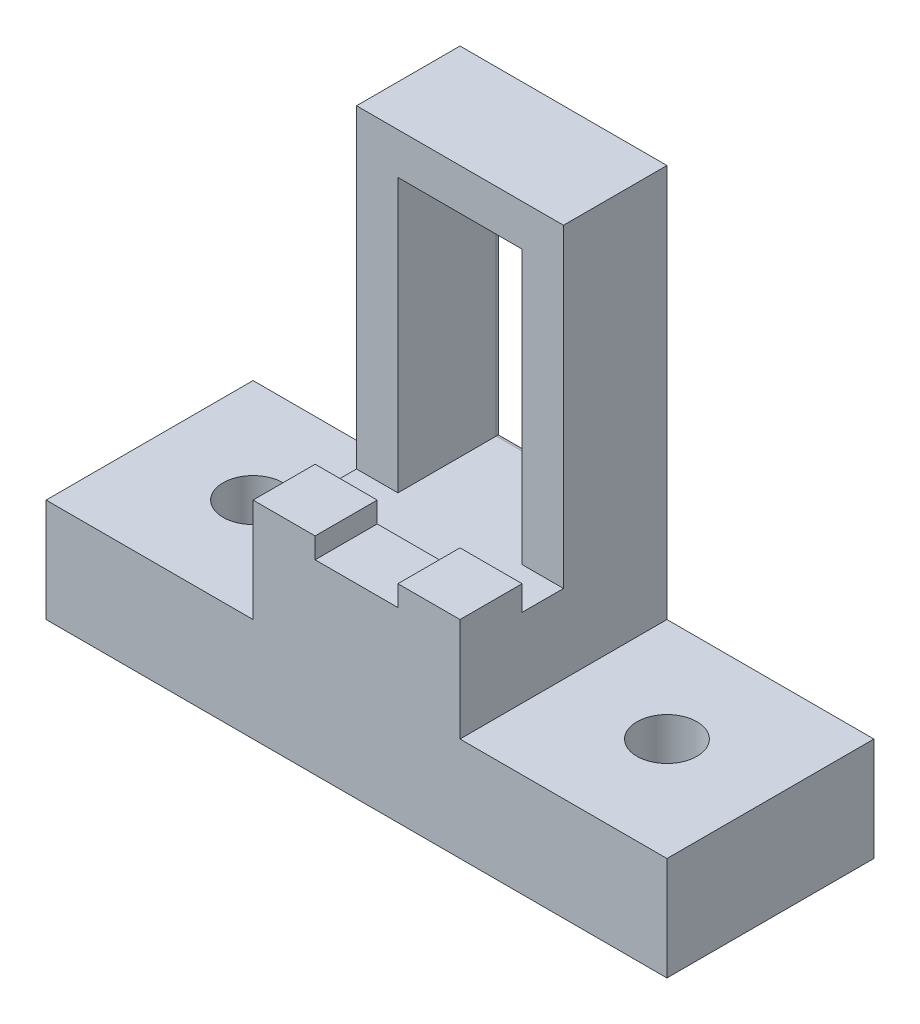
SolidWorks part; units mm, degrees
other "标注1"
sketch "草图8" plane through (-30, 24, -10.05) normal (-0.0333, 0.0376, -0.9987) x (-0.9561, 0.2897, 0.0428)
sketch "草图10" plane through (-30, 24, -10.05) normal (-0.0333, 0.0376, -0.9987) x (-0.9561, 0.2897, 0.0428)
sketch "草图23" plane through (-30, 24, -10) normal (-0.0333, 0.0376, -0.9987) x (-0.9561, 0.2897, 0.0428)
sketch "草图26" plane through (-30, 24, -10) normal (-0.0333, 0.0376, -0.9987) x (-0.9561, 0.2897, 0.0428)
sketch "草图30" plane through (-30, 24, -10) normal (-0.0333, 0.0376, -0.9987) x (-0.9561, 0.2897, 0.0428)
sketch "草图33" plane through (-30, 24, -10) normal (-0.0333, 0.0376, -0.9987) x (-0.9561, 0.2897, 0.0428)
other "标注2"
sketch "草图16" plane through (0, 24, 0) normal (0.8795, 0.3038, 0.3663) x (0.4513, -0.2881, -0.8446)
sketch "草图24" plane through (0, 24, 0) normal (0.8795, 0.3038, 0.3663) x (0.4513, -0.2881, -0.8446)
sketch "草图27" plane through (0, 24, 0) normal (0.8795, 0.3038, 0.3663) x (0.4513, -0.2881, -0.8446)
sketch "草图31" plane through (0, 24, 0) normal (0.8795, 0.3038, 0.3663) x (0.4513, -0.2881, -0.8446)
sketch "草图34" plane through (0, 24, 0) normal (0.8795, 0.3038, 0.3663) x (0.4513, -0.2881, -0.8446)
other "标注3"
sketch "草图17" plane through (0, 24, 0) normal (0.8795, 0.3038, 0.3663) x (0.4513, -0.2881, -0.8446)
sketch "草图25" plane through (0, 24, 0) normal (0.8795, 0.3038, 0.3663) x (0.4513, -0.2881, -0.8446)
sketch "草图28" plane through (0, 24, 0) normal (0.8795, 0.3038, 0.3663) x (0.4513, -0.2881, -0.8446)
sketch "草图32" plane through (0, 24, 0) normal (0.8795, 0.3038, 0.3663) x (0.4513, -0.2881, -0.8446)
sketch "草图35" plane through (0, 24, 0) normal (0.8795, 0.3038, 0.3663) x (0.4513, -0.2881, -0.8446)
ref_plane "前视基准面" through (0, 0, 0) normal (0, 0, 1) x (1, 0, 0)
ref_plane "上视基准面" through (0, 0, 0) normal (0, 1, 0) x (1, 0, 0)
ref_plane "右视基准面" through (0, 0, 0) normal (1, 0, 0) x (0, 0, -1)
other "Configuration Table"
sketch "草图1" plane through (0, 0, 0) normal (0, 1, 0) x (1, 0, 0)
  line L0 (-20, 0) -> (-20, -5)
  line L2 (0, 0) -> (0, 10)
  line L3 (0, 10) -> (-30, 10)
  line L4 (-30, 0) -> (-30, 10)
  line L5 (-20, -5) -> (-10, -5)
  line L6 (-10, -5) -> (-10, 0)
  line L7 (-30, 0) -> (-20, 0)
  line L8 (-10, 0) -> (0, 0)
  dimension "D1" = 10
  dimension "D2" = 30
  dimension "D3" = 10
  dimension "D4" = 10
  dimension "D5" = 5
  dimension "D6" = 5
extrude "凸台-拉伸1" add sketch "草图1" along normal blind 4
sketch "草图2" plane through (0, 4, 0) normal (0, 1, 0) x (1, 0, 0)
  line L7 (0, 10) -> (-30, 10) construction
  line L8 (-20, -5) -> (-10, -5)
  line L9 (-20, -5) -> (-20, 10)
  line L10 (-20, 10) -> (-10, 10)
  line L11 (-10, -5) -> (-10, 10)
extrude "凸台-拉伸2" add sketch "草图2" along normal blind 20
sketch "草图3" plane through (0, 4, 0) normal (0, 1, 0) x (1, 0, 0)
  line L0 (-20, 10) -> (-30, 10) construction
  line L1 (-30, 10) -> (-30, 0) construction
  line L2 (0, 10) -> (-10, 10) construction
  line L3 (0, 0) -> (0, 10) construction
  circle A0 centre (-25, 5) radius 1.45
  circle A1 centre (-5, 5) radius 1.45
  dimension "D1" = 5
  dimension "D2" = 5
  dimension "D3" = 5
  dimension "D4" = 5
  dimension "D5" = 2.9
  dimension "D6" = 2.9
extrude "切除-拉伸1" cut sketch "草图3" against normal blind 20
sketch "草图4" plane through (0, 0, -10) normal (0, 0, -1) x (-1, 0, 0)
  line L6 (10, 24) -> (10, 4) construction
  line L7 (12, 22) -> (18, 22)
  line L8 (12, 22) -> (12, 8.8)
  line L9 (12, 8.8) -> (18, 8.8)
  line L10 (18, 22) -> (18, 8.8)
  line L11 (10, 24) -> (20, 24) construction
  dimension "D1" = 6
  dimension "D2" = 13.2
  dimension "D3" = 2
  dimension "D4" = 2
extrude "切除-拉伸2" cut sketch "草图4" against normal blind 9.5
sketch "草图6" plane through (0, 0, -0.5) normal (0, 0, -1) x (-1, 0, 0)
  line L0 (15, 22) -> (15, 20.68) construction
  line L1 (18, 22) -> (12, 22) construction
  line L2 (15, 20.68) -> (15, 15.6) construction
  line L3 (15, 15.6) -> (15, 10.52) construction
  circle A0 centre (15, 20.68) radius 0.75
  circle A2 centre (15, 10.52) radius 0.75
  circle A3 centre (15, 15.6) radius 0.75
  dimension "D4" = 1.5
  dimension "D5" = 1.5
  dimension "D6" = 1.5
  dimension "D1" = 1.32
  dimension "D2" = 5.08
  dimension "D3" = 5.08
extrude "切除-拉伸4" cut sketch "草图6" against normal blind 3.5
sketch "草图7" plane through (0, 0, 5) normal (0, 0, 1) x (1, 0, 0)
  line L4 (-10, 24) -> (-20, 24)
  line L5 (-20, 24) -> (-20, 0)
  line L6 (-20, 0) -> (-10, 0)
  line L7 (-10, 0) -> (-10, 24)
  line L8 (-10, 24) -> (-20, 24)
  line L9 (-20, 24) -> (-20, 0)
  line L10 (-20, 0) -> (-10, 0)
  line L11 (-10, 0) -> (-10, 24)
  dimension "D1" = 0
extrude "切除-拉伸5" cut sketch "草图7" against normal blind 5
sketch "草图9" plane through (0, 0, -0.5) normal (0, 0, -1) x (-1, 0, 0)
  line L1 (13.5, 21.6) -> (16.5, 21.6)
  line L2 (13.5, 21.6) -> (13.5, 9.6)
  line L3 (13.5, 9.6) -> (16.5, 9.6)
  line L4 (16.5, 21.6) -> (16.5, 9.6)
  line L5 (13.5, 21.6) -> (16.5, 9.6) construction
  line L6 (13.5, 9.6) -> (16.5, 21.6) construction
  point P0 (15, 15.6)
  dimension "D1" = 3
  dimension "D2" = 12
extrude "切除-拉伸6" cut sketch "草图9" against normal blind 10
sketch "草图11" plane through (0, 0, -0.5) normal (0, 0, -1) x (-1, 0, 0)
  line L0 (18, 8.8) -> (18, 22) construction
  line L1 (16.5, 21.6) -> (18, 21.6)
  line L2 (16.5, 21.6) -> (16.5, 9.6)
  line L3 (16.5, 9.6) -> (18, 9.6)
  line L4 (18, 21.6) -> (18, 9.6)
  line L5 (12, 22) -> (12, 8.8) construction
  line L6 (13.5, 21.6) -> (12, 21.6)
  line L7 (13.5, 21.6) -> (13.5, 9.6)
  line L8 (13.5, 9.6) -> (12, 9.6)
  line L9 (12, 21.6) -> (12, 9.6)
extrude "切除-拉伸7" cut sketch "草图11" against normal blind 10
sketch "草图13" plane through (0, 24, 0) normal (0, 1, 0) x (1, 0, 0)
  line L0 (-10, 0) -> (-10, 10) construction
  line L1 (-20, 0) -> (-10, 0)
  line L2 (-20, 0) -> (-20, 5)
  line L3 (-20, 5) -> (-10, 5)
  line L4 (-10, 0) -> (-10, 5)
extrude "切除-拉伸8" cut sketch "草图13" against normal up to surface (20 mm away) up to face at (-5, 4, -3.55)
sketch "草图19" plane through (0, 4, 0) normal (0, 1, 0) x (1, 0, 0)
  line L1 (-20, 5) -> (-10, 5)
  line L2 (-20, 5) -> (-20, 2.6)
  line L3 (-20, 2.6) -> (-10, 2.6)
  line L4 (-10, 5) -> (-10, 2.6)
  dimension "D1" = 2.4
extrude "凸台-拉伸6" add sketch "草图19" along normal blind 4.8
sketch "草图20" plane through (0, 4, 0) normal (0, 1, 0) x (1, 0, 0)
  line L0 (-30, 0) -> (0, 0) construction
  line L1 (-20, 2.6) -> (-10, 2.6)
  line L2 (-20, 2.6) -> (-20, 0)
  line L3 (-20, 0) -> (-10, 0)
  line L4 (-10, 2.6) -> (-10, 0)
extrude "凸台-拉伸7" add sketch "草图20" along normal blind 6
fillet "圆角17" radius 0.25 4 edges at (-15, 8.8, -10) (-15, 22, -10) (-18, 15.4, -10) (-12, 15.4, -10)
sketch "草图21" plane through (0, 0, 0) normal (0, 0, 1) x (1, 0, 0)
  line L0 (-15, 10) -> (-15, 7.5151) construction
  line L1 (-20, 10) -> (-10, 10) construction
  line L2 (-13, 10) -> (-17, 10)
  line L3 (-17, 10) -> (-17, 9)
  line L4 (-17, 9) -> (-13, 9)
  line L5 (-13, 10) -> (-13, 9)
  point P9 (-15, 9)
  dimension "D1" = 2
  dimension "D2" = 1
extrude "切除-拉伸9" cut sketch "草图21" against normal blind 5.2
sketch "草图22" plane through (0, 0, -2.6) normal (0, 0, -1) x (-1, 0, 0)
  line L8 (17, 9) -> (13, 9)
  line L9 (13, 9) -> (13, 10)
  line L10 (13, 10) -> (10, 10)
  line L11 (10, 10) -> (10, 8.8)
  line L12 (10, 8.8) -> (20, 8.8)
  line L13 (20, 8.8) -> (20, 10)
  line L14 (20, 10) -> (17, 10)
  line L15 (17, 10) -> (17, 9)
  line L16 (17, 9) -> (13, 9)
  line L17 (13, 9) -> (13, 10)
  line L18 (13, 10) -> (10, 10)
  line L19 (10, 10) -> (10, 8.8)
  line L20 (10, 8.8) -> (20, 8.8)
  line L21 (20, 8.8) -> (20, 10)
  line L22 (20, 10) -> (17, 10)
  line L23 (17, 10) -> (17, 9)
  dimension "D1" = 0
extrude "凸台-拉伸8" add sketch "草图22" along normal blind 0.4
sketch "草图29" plane through (0, 4, 0) normal (0, 1, 0) x (1, 0, 0)
  line L0 (-30, 0) -> (-20, 0) construction
  line L1 (-20, 0) -> (-20, 10) construction
  line L2 (-20, 10) -> (-30, 10) construction
  line L3 (-30, 10) -> (-30, 0) construction
  line L4 (-10, 10) -> (-10, 0) construction
  line L5 (-10, 0) -> (0, 0) construction
  line L6 (0, 0) -> (0, 10) construction
  line L7 (0, 10) -> (-10, 10) construction
  line L8 (-30, 0) -> (-20, 0)
  line L9 (-20, 0) -> (-20, 10)
  line L10 (-20, 10) -> (-30, 10)
  line L11 (-30, 10) -> (-30, 0)
  line L12 (-10, 10) -> (-10, 0)
  line L13 (-10, 0) -> (0, 0)
  line L14 (0, 0) -> (0, 10)
  line L15 (0, 10) -> (-10, 10)
  circle A0 centre (-5, 5) radius 1.45 construction
  circle A1 centre (-25, 5) radius 1.45 construction
  circle A2 centre (-5, 5) radius 1.45
  circle A3 centre (-25, 5) radius 1.45
extrude "凸台-拉伸9" add sketch "草图29" along normal blind 1
